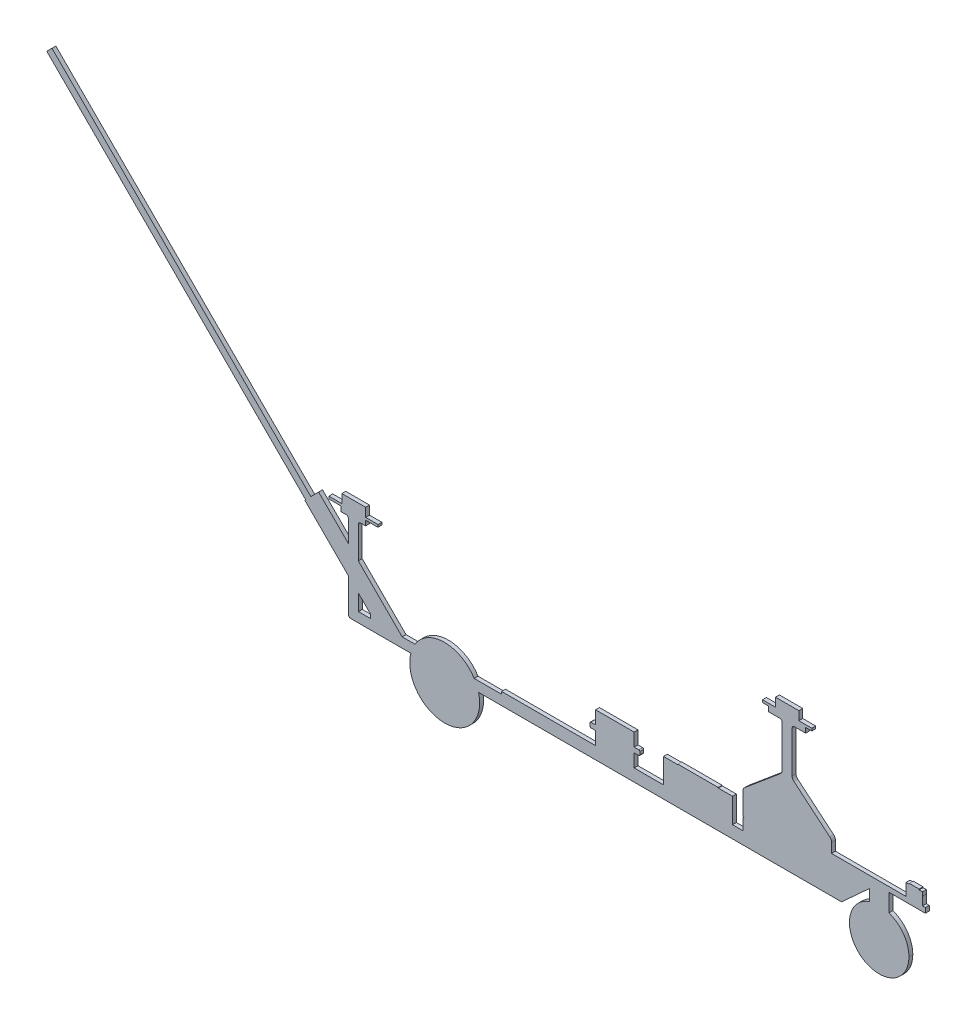
SolidWorks part; units mm, degrees
ref_plane "Front Plane" through (0, 0, 0) normal (0, 0, 1) x (1, 0, 0)
ref_plane "Top Plane" through (0, 0, 0) normal (0, 1, 0) x (1, 0, 0)
ref_plane "Right Plane" through (0, 0, 0) normal (1, 0, 0) x (0, 0, -1)
sketch "Sketch1" plane through (0, 0, 0) normal (0, 0, 1) x (1, 0, 0)
  line L4 (267.7006, -317.4638) -> (267.7006, -312.0788)
  line L5 (270.2406, -309.5388) -> (270.2595, -309.5388)
  line L6 (270.2595, -309.5388) -> (274.9226, -309.5388)
  line L7 (274.9226, -309.5388) -> (282.2301, -309.5388)
  line L8 (282.2301, -309.5388) -> (282.2301, -275.8628)
  line L9 (282.2301, -275.8628) -> (287.3396, -275.8628)
  line L10 (287.3396, -275.8628) -> (290.0913, -275.8628)
  line L11 (290.0913, -275.8628) -> (379.171, -275.8628)
  line L12 (379.171, -275.8628) -> (381.4896, -275.8628)
  line L13 (381.4896, -275.8628) -> (381.4896, -309.5388)
  line L14 (381.4896, -309.5388) -> (385.4176, -309.5388)
  line L15 (385.4176, -309.5388) -> (389.2332, -309.5388)
  line L16 (389.2332, -309.5388) -> (393.4792, -309.5388)
  line L17 (396.0192, -312.0788) -> (396.0192, -317.4638)
  line L31 (1107.8483, -258.9171) -> (1115.6483, -258.9171)
  line L32 (1115.6483, -258.9171) -> (1115.6483, -260.9171)
  line L33 (1115.6483, -260.9171) -> (1124.1483, -260.9171)
  line L34 (1124.1483, -260.9171) -> (1124.1483, -270.6171)
  line L35 (1124.1483, -270.6171) -> (1123.8483, -270.9171)
  line L36 (1123.8483, -270.9171) -> (1124.1483, -270.9171)
  line L37 (1124.1483, -270.9171) -> (1124.1483, -287.6171)
  line L42 (1082.1483, -287.6171) -> (1082.1483, -270.9171)
  line L43 (1082.1483, -270.9171) -> (1082.4483, -270.9171)
  line L44 (1082.4483, -270.9171) -> (1082.1483, -270.6171)
  line L45 (1082.1483, -270.6171) -> (1082.1483, -260.9171)
  line L46 (1082.1483, -260.9171) -> (1082.7978, -260.9171)
  line L47 (1082.7978, -260.9171) -> (1085.0939, -260.9171)
  line L48 (1085.0939, -260.9171) -> (1090.6483, -260.9171)
  line L49 (1090.6483, -260.9171) -> (1090.6483, -258.9171)
  line L50 (1090.6483, -258.9171) -> (1107.8483, -258.9171)
  line L56 (393.4792, -322.2138) -> (388.9514, -322.2138)
  line L57 (388.9514, -322.2138) -> (385.4176, -322.2138)
  line L58 (385.4176, -322.2138) -> (381.4896, -322.2138)
  line L59 (381.4896, -322.2138) -> (381.4896, -355.8898)
  line L60 (381.4896, -355.8898) -> (457.116, -355.8898)
  line L61 (457.116, -355.8898) -> (457.116, -349.5398)
  line L62 (457.116, -349.5398) -> (457.116, -292.3898)
  line L63 (457.116, -292.3898) -> (476.42, -292.3898)
  line L64 (476.42, -292.3898) -> (488.866, -292.3898)
  line L65 (488.866, -292.3898) -> (493.946, -292.3898)
  line L66 (493.946, -292.3898) -> (493.946, -291.1198)
  line L67 (493.946, -291.1198) -> (598.086, -291.1198)
  line L68 (598.086, -291.1198) -> (598.086, -292.3898)
  line L69 (598.086, -292.3898) -> (603.166, -292.3898)
  line L70 (603.166, -292.3898) -> (615.612, -292.3898)
  line L71 (615.612, -292.3898) -> (634.916, -292.3898)
  line L72 (634.916, -292.3898) -> (634.916, -349.5398)
  line L73 (634.916, -349.5398) -> (634.916, -355.8898)
  line L74 (634.916, -355.8898) -> (657.0313, -355.8898)
  line L75 (657.0313, -355.8898) -> (658.4006, -355.8898)
  line L76 (658.4006, -355.8898) -> (659.9006, -355.8898)
  line L77 (659.9006, -355.8898) -> (661.4006, -355.8898)
  line L78 (661.4006, -355.8898) -> (661.4006, -329.3398)
  line L79 (666.3238, -324.1472) -> (661.4006, -324.1398)
  line L80 (661.4006, -324.1398) -> (661.4006, -267.4177)
  line L81 (665.9372, -257.6889) -> (758.464, -180.0497)
  line L82 (763.0006, -170.3209) -> (763.0006, -63.7898)
  line L83 (756.6506, -57.4398) -> (728.0756, -57.4398)
  line L84 (728.0756, -57.4398) -> (728.0756, -44.7398)
  line L85 (728.0756, -44.7398) -> (712.2006, -44.7398)
  line L86 (712.2006, -44.7398) -> (712.2006, -38.3898)
  line L87 (712.2006, -38.3898) -> (745.7006, -38.3898)
  line L88 (745.7006, -38.3898) -> (745.7006, -34.8898)
  line L92 (745.7006, -34.8898) -> (745.7006, -15.8898)
  line L93 (745.7006, -15.8898) -> (748.6295, -15.8898)
  line L94 (748.6295, -15.8898) -> (752.7717, -15.8898)
  line L95 (752.7717, -15.8898) -> (759.8427, -15.8898)
  line L96 (759.8427, -15.8898) -> (791.5585, -15.8898)
  line L97 (791.5585, -15.8898) -> (798.6295, -15.8898)
  line L98 (798.6295, -15.8898) -> (802.7717, -15.8898)
  line L99 (802.7717, -15.8898) -> (805.7006, -15.8898)
  line L100 (805.7006, -15.8898) -> (805.7006, -38.3898)
  line L101 (805.7006, -38.3898) -> (839.2006, -38.3898)
  line L102 (839.2006, -38.3898) -> (839.2006, -44.7398)
  line L103 (839.2006, -44.7398) -> (823.3256, -44.7398)
  line L104 (823.3256, -44.7398) -> (823.3256, -57.4398)
  line L105 (823.3256, -57.4398) -> (794.7506, -57.4398)
  line L106 (788.4006, -63.7898) -> (788.4006, -170.3209)
  line L107 (792.9372, -180.0497) -> (885.464, -257.6889)
  line L108 (890.0006, -267.4177) -> (890.0006, -292.3671)
  line L109 (890.0006, -292.3671) -> (902.7006, -292.3671)
  line L110 (902.7006, -292.3671) -> (990.6888, -292.3671)
  line L111 (990.6888, -292.3671) -> (1016.0888, -292.3671)
  line L112 (1016.0888, -292.3671) -> (1049.5098, -292.3671)
  line L113 (1049.5098, -292.3671) -> (1070.4823, -292.3671)
  line L114 (1070.4823, -292.3671) -> (1082.1483, -292.3671)
  line L115 (1124.1483, -292.3671) -> (1131.7313, -292.3671)
  line L116 (1131.7313, -292.3671) -> (1131.7313, -305.0671)
  line L117 (1131.7313, -305.0671) -> (1120.1381, -305.0671)
  line L118 (1120.1381, -305.0671) -> (1070.913, -305.0671)
  line L119 (1070.913, -305.0671) -> (1049.9405, -305.0671)
  line L120 (1049.9405, -305.0671) -> (1038.3071, -305.0671)
  line L125 (1038.3071, -308.9838) -> (1037.9529, -350.9577)
  line L126 (1037.9529, -350.9577) -> (1037.9529, -334.3838)
  line L128 (987.1534, -351.082) -> (987.1534, -322.2385)
  line L129 (987.1534, -322.2385) -> (916.9238, -386.6157)
  line L130 (914.3492, -387.6171) -> (903.1313, -387.6171)
  line L131 (903.1313, -387.6171) -> (890.4313, -387.6171)
  line L132 (1038.3071, -305.0671) -> (1038.3071, -308.9838)
  line L133 (890.4313, -387.6171) -> (-19.3061, -387.6398)
  line L139 (-354.1687, -382.4398) -> (-354.1687, -367.4398)
  line L140 (-354.1687, -295.6583) -> (-354.1687, -367.4398)
  line L141 (-298.2951, -362.2398) -> (-298.2951, -351.5318)
  line L142 (-298.2951, -351.5318) -> (-328.7687, -321.0583)
  line L143 (-328.7687, -321.0583) -> (-328.7687, -362.2286)
  line L144 (1124.1483, -287.6171) -> (1124.1483, -292.3671)
  line L145 (-298.2951, -362.2398) -> (-328.7687, -362.2286)
  line L146 (1082.1483, -287.6171) -> (1082.1483, -292.3671)
  line L147 (-348.9687, -387.6398) -> (-193.7314, -387.6398)
  line L148 (-354.1687, -295.6583) -> (-467.1923, -182.6347)
  line L149 (-467.1923, -182.6347) -> (-464.9473, -180.3896)
  line L150 (-464.9473, -180.3896) -> (-1131.7313, 486.3944)
  line L151 (-1131.7313, 486.3944) -> (-1130.5998, 487.5259)
  line L152 (-1130.5998, 487.5259) -> (-1119.3924, 498.7333)
  line L153 (-1119.3924, 498.7333) -> (-1118.2609, 499.8648)
  line L154 (-1118.2609, 499.8648) -> (-451.4769, -166.9192)
  line L155 (-451.4769, -166.9192) -> (-431.2713, -146.7136)
  line L156 (-431.2713, -146.7136) -> (-354.1687, -223.8162)
  line L157 (-354.1687, -223.8162) -> (-354.1687, -168.1167)
  line L158 (-360.5187, -161.7667) -> (-373.2187, -161.7667)
  line L159 (-373.2187, -161.7667) -> (-373.2187, -149.0667)
  line L160 (-373.2187, -149.0667) -> (-404.9687, -149.0667)
  line L161 (-404.9687, -149.0667) -> (-404.9687, -142.7167)
  line L162 (-404.9687, -142.7167) -> (-371.4687, -142.7167)
  line L163 (-371.4687, -142.7167) -> (-371.4687, -120.2167)
  line L176 (-310.1494, -142.7167) -> (-278.3994, -142.7167)
  line L177 (-278.3994, -142.7167) -> (-278.3994, -149.0667)
  line L178 (-278.3994, -149.0667) -> (-310.1494, -149.0667)
  line L179 (-310.1494, -149.0667) -> (-310.1494, -161.7667)
  line L180 (-310.1494, -161.7667) -> (-322.8494, -161.7667)
  line L181 (-329.1994, -168.1167) -> (-329.1994, -249.2162)
  line L182 (-329.1994, -249.2162) -> (-216.1758, -362.2398)
  line L183 (-216.1758, -362.2398) -> (-183.316, -362.2398)
  line L184 (-30.5828, -362.2398) -> (39.8743, -362.2398)
  line L185 (39.8743, -362.2398) -> (39.8743, -355.8898)
  line L186 (39.8743, -355.8898) -> (41.8743, -355.8898)
  line L187 (41.8743, -355.8898) -> (47.8743, -355.8898)
  line L188 (47.8743, -355.8898) -> (49.8743, -355.8898)
  line L189 (49.8743, -355.8898) -> (52.0487, -355.8898)
  line L190 (52.0487, -355.8898) -> (282.2301, -355.8898)
  line L191 (282.2301, -355.8898) -> (282.2301, -322.2138)
  line L192 (282.2301, -322.2138) -> (279.8681, -322.2138)
  line L193 (279.8681, -322.2138) -> (274.4947, -322.2138)
  line L194 (274.4947, -322.2138) -> (274.4764, -322.2138)
  line L195 (274.4764, -322.2138) -> (270.2595, -322.2138)
  line L196 (270.2595, -322.2138) -> (270.2406, -322.2138)
  line L197 (267.7006, -319.6738) -> (267.7006, -317.4638)
  line L204 (396.0192, -317.4638) -> (396.0192, -319.6738)
  line L205 (-310.1494, -120.2167) -> (-371.4687, -120.2167)
  line L206 (-310.1494, -120.2167) -> (-310.1494, -142.7167)
  arc A0 (270.2406, -309.5388) -> (267.7006, -312.0788) centre (270.2406, -312.0788) ccw
  arc A1 (396.0192, -312.0788) -> (393.4792, -309.5388) centre (393.4792, -312.0788) ccw
  arc A2 (661.4715, -328.4838) -> (661.4006, -329.3398) centre (666.6006, -329.3398) ccw
  arc A3 (661.4743, -328.4671) -> (661.4715, -328.4838) centre (666.6006, -329.3398) ccw
  arc A4 (661.5597, -328.0632) -> (661.4743, -328.4671) centre (666.6006, -329.3398) ccw
  arc A5 (661.5777, -327.9941) -> (661.5597, -328.0632) centre (666.6006, -329.3398) ccw
  arc A6 (661.6824, -327.6512) -> (661.5777, -327.9941) centre (666.6006, -329.3398) ccw
  arc A7 (661.7141, -327.5615) -> (661.6824, -327.6512) centre (666.6006, -329.3398) ccw
  arc A8 (661.8386, -327.2509) -> (661.7141, -327.5615) centre (666.6006, -329.3398) ccw
  arc A9 (661.8877, -327.1425) -> (661.8386, -327.2509) centre (666.6006, -329.3398) ccw
  arc A10 (662.0274, -326.8647) -> (661.8877, -327.1425) centre (666.6006, -329.3398) ccw
  arc A11 (662.0971, -326.7401) -> (662.0274, -326.8647) centre (666.6006, -329.3398) ccw
  arc A12 (662.2474, -326.4955) -> (662.0971, -326.7401) centre (666.6006, -329.3398) ccw
  arc A13 (662.3408, -326.3575) -> (662.2474, -326.4955) centre (666.6006, -329.3398) ccw
  arc A14 (662.4972, -326.1458) -> (662.3408, -326.3575) centre (666.6006, -329.3398) ccw
  arc A15 (662.6169, -325.9976) -> (662.4972, -326.1458) centre (666.6006, -329.3398) ccw
  arc A16 (662.7749, -325.8178) -> (662.6169, -325.9976) centre (666.6006, -329.3398) ccw
  arc A17 (662.9234, -325.6631) -> (662.7749, -325.8178) centre (666.6006, -329.3398) ccw
  arc A18 (663.0788, -325.5139) -> (662.9234, -325.6631) centre (666.6006, -329.3398) ccw
  arc A19 (663.2579, -325.3566) -> (663.0788, -325.5139) centre (666.6006, -329.3398) ccw
  arc A20 (663.4068, -325.2362) -> (663.2579, -325.3566) centre (666.6006, -329.3398) ccw
  arc A21 (663.6177, -325.0804) -> (663.4068, -325.2362) centre (666.6006, -329.3398) ccw
  arc A22 (663.7566, -324.9864) -> (663.6177, -325.0804) centre (666.6006, -329.3398) ccw
  arc A23 (664.0004, -324.8366) -> (663.7566, -324.9864) centre (666.6006, -329.3398) ccw
  arc A24 (664.1258, -324.7665) -> (664.0004, -324.8366) centre (666.6006, -329.3398) ccw
  arc A25 (664.4028, -324.6271) -> (664.1258, -324.7665) centre (666.6006, -329.3398) ccw
  arc A26 (664.5119, -324.5777) -> (664.4028, -324.6271) centre (666.6006, -329.3398) ccw
  arc A27 (664.8219, -324.4535) -> (664.5119, -324.5777) centre (666.6006, -329.3398) ccw
  arc A28 (664.9122, -324.4215) -> (664.8219, -324.4535) centre (666.6006, -329.3398) ccw
  arc A29 (665.2546, -324.317) -> (664.9122, -324.4215) centre (666.6006, -329.3398) ccw
  arc A30 (665.3241, -324.2989) -> (665.2546, -324.317) centre (666.6006, -329.3398) ccw
  arc A31 (665.6975, -324.2188) -> (665.3241, -324.2989) centre (666.6006, -329.3398) ccw
  arc A32 (665.7448, -324.2107) -> (665.6975, -324.2188) centre (666.6006, -329.3398) ccw
  arc A33 (666.1473, -324.1596) -> (665.7448, -324.2107) centre (666.6006, -329.3398) ccw
  arc A34 (666.1712, -324.1576) -> (666.1473, -324.1596) centre (666.6006, -329.3398) ccw
  arc A35 (666.3238, -324.1472) -> (666.1712, -324.1576) centre (666.6006, -329.3398) ccw
  arc A36 (665.9372, -257.6889) -> (661.4006, -267.4177) centre (674.1006, -267.4177) ccw
  arc A37 (758.464, -180.0497) -> (763.0006, -170.3209) centre (750.3006, -170.3209) ccw
  arc A38 (763.0006, -63.7898) -> (756.6506, -57.4398) centre (756.6506, -63.7898) ccw
  arc A39 (794.7506, -57.4398) -> (788.4006, -63.7898) centre (794.7506, -63.7898) ccw
  arc A40 (788.4006, -170.3209) -> (792.9372, -180.0497) centre (801.1006, -170.3209) ccw
  arc A41 (890.0006, -267.4177) -> (885.464, -257.6889) centre (877.3006, -267.4177) ccw
  arc A42 (914.3492, -387.6171) -> (916.9238, -386.6157) centre (914.3492, -383.8071) ccw
  arc A43 (-354.1687, -382.4398) -> (-348.9687, -387.6398) centre (-348.9687, -382.4398) ccw
  arc A82 (-193.7314, -387.6398) -> (-19.3061, -387.6398) centre (-106.5187, -409.8648) ccw
  arc A159 (-354.1687, -168.1167) -> (-360.5187, -161.7667) centre (-360.5187, -168.1167) ccw
  arc A160 (-322.8494, -161.7667) -> (-329.1994, -168.1167) centre (-322.8494, -168.1167) ccw
  arc A161 (-30.5828, -362.2398) -> (-183.316, -362.2398) centre (-106.9494, -409.8648) ccw
  arc A162 (267.7006, -319.6738) -> (270.2406, -322.2138) centre (270.2406, -319.6738) ccw
  arc A163 (393.4792, -322.2138) -> (396.0192, -319.6738) centre (393.4792, -319.6738) ccw
  spline S2 degree 3 poles (936.0984, -423.2838) (936.0985, -390.3936) (954.8422, -362.5051) (987.1534, -351.082) knots 0 0 0 0 0.773473 0.773473 0.773473 0.773473 weights 1 0.84897 0.814758 0.897363
  spline S3 degree 3 poles (1012.6786, -346.7029) (1012.7131, -346.7028) (1012.7475, -346.7028) (1012.7819, -346.7028) knots 0 0 0 0 1 1 1 1 weights 1 1 1 1
  spline S4 degree 3 poles (1037.9529, -350.9577) (1070.4609, -362.2714) (1089.3621, -390.2375) (1089.3621, -423.2838) knots 0.223415 0.223415 0.223415 0.223415 1 1 1 1 weights 0.898366 0.814484 0.848362 1
  spline S5 degree 3 poles (1089.3621, -423.2838) (1089.3621, -468.1439) (1057.6415, -499.8647) (1012.7819, -499.8647) knots 0 0 0 0 1 1 1 1 weights 1 0.804738 0.804738 1
  spline S6 degree 3 poles (1012.7819, -499.8647) (1012.7475, -499.8648) (1012.7131, -499.8648) (1012.6786, -499.8648) knots 0 0 0 0 1 1 1 1 weights 1 1 1 1
  spline S7 degree 3 poles (1012.6786, -499.8648) (967.819, -499.8648) (936.0984, -468.1439) (936.0984, -423.2838) knots 0 0 0 0 1 1 1 1 weights 1 0.804738 0.804738 1
extrude "Boss-Extrude1" add sketch "Sketch1" along normal blind 10
